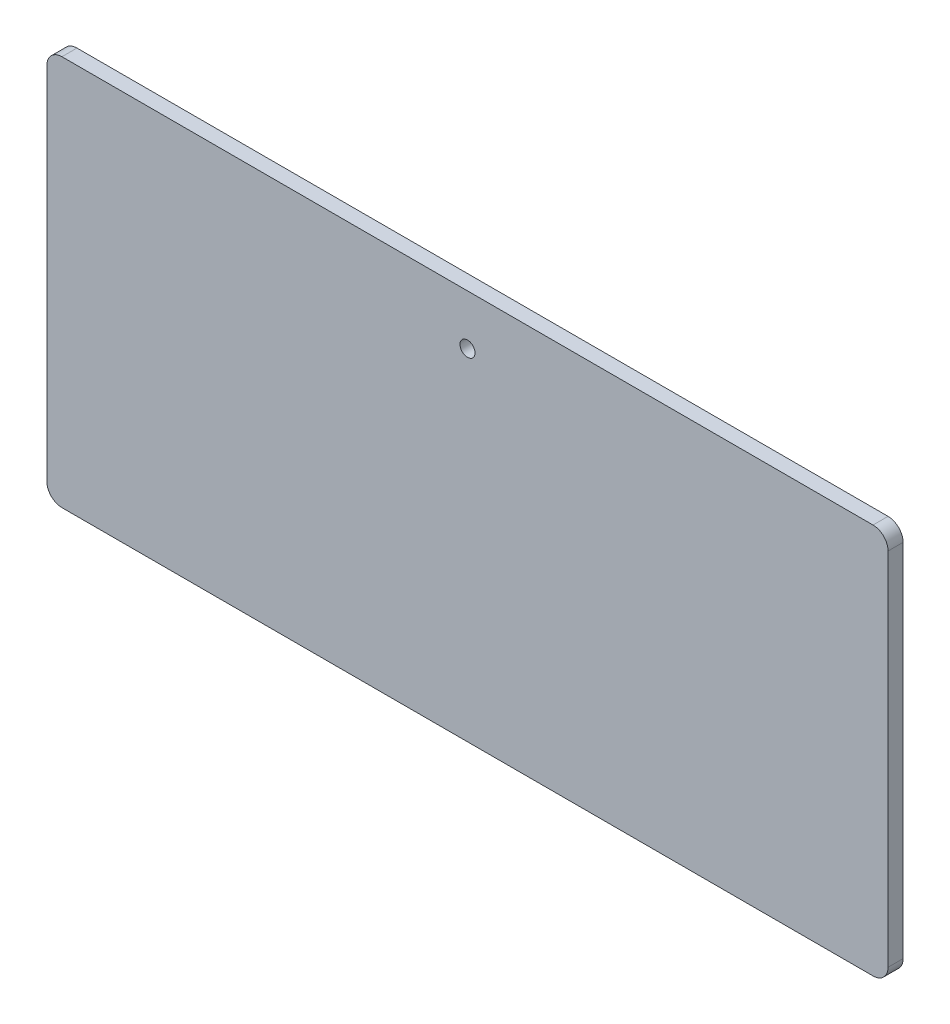
SolidWorks part; units mm, degrees
ref_plane "Plan de face" through (0, 0, 0) normal (0, 0, 1) x (1, 0, 0)
ref_plane "Plan de dessus" through (0, 0, 0) normal (0, 1, 0) x (1, 0, 0)
ref_plane "Plan de droite" through (0, 0, 0) normal (1, 0, 0) x (0, 0, -1)
sketch "Esquisse1" plane through (0, 0, 0) normal (0, 0, 1) x (1, 0, 0)
  line L1 (0, 0) -> (168, 0)
  line L2 (0, 0) -> (0, 78)
  line L3 (0, 78) -> (168, 78)
  line L4 (168, 0) -> (168, 78)
  dimension "D1" = 168
  dimension "D2" = 78
extrude "Boss.-Extru.1" add sketch "Esquisse1" along normal blind 3
fillet "Congé1" radius 3 4 edges at (0, 78, 1.5) (0, 0, 1.5) (168, 0, 1.5) (168, 78, 1.5)
sketch "Esquisse2" plane through (0, 0, 3) normal (0, 0, 1) x (1, 0, 0)
  line L0 (84, 78) -> (84, 68) construction
  line L1 (165, 78) -> (3, 78) construction
  circle A0 centre (84, 68) radius 1.5
  dimension "D1" = 3
  dimension "D2" = 10
extrude "Enlèv. mat.-Extru.1" cut sketch "Esquisse2" against normal through all
